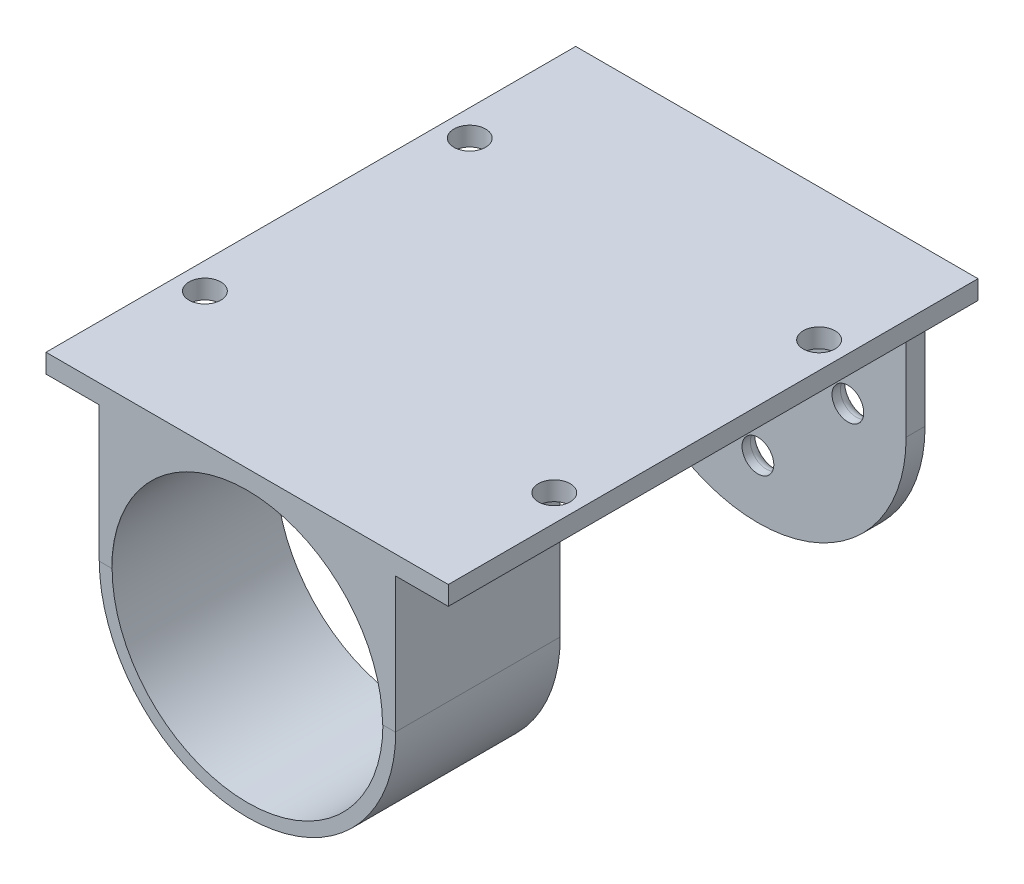
SolidWorks part; units mm, degrees
ref_plane "Front Plane" through (0, 0, 0) normal (0, 0, 1) x (1, 0, 0)
ref_plane "Top Plane" through (0, 0, 0) normal (0, 1, 0) x (1, 0, 0)
ref_plane "Right Plane" through (0, 0, 0) normal (1, 0, 0) x (0, 0, -1)
sketch "Sketch1" plane through (0, 0, 0) normal (0, 0, 1) x (1, 0, 0)
  circle A0 centre (0, 0) radius 14
  dimension "D1" = 28
extrude "Boss-Extrude1" add sketch "Sketch1" along normal blind 50
sketch "Sketch5" plane through (0, 0, 0) normal (0, 1, 0) x (1, 0, 0)
  line L0 (-14, 0) -> (14, 0)
  line L1 (-14, 0) -> (-14, -50.0349)
  line L2 (14, 0) -> (14, -50.0349)
  line L3 (-14, -50.0349) -> (14, -50.0349)
extrude "Boss-Extrude2" add sketch "Sketch5" along normal blind 21
sketch "Sketch2" plane through (0, 0, 50) normal (0, 0, 1) x (1, 0, 0)
  circle A0 centre (0, 0) radius 12.7918
  circle A1 centre (0, 0) radius 14 construction
  dimension "D1" = 1.2082
  dimension "D2" = 1.2082
extrude "Cut-Extrude1" cut sketch "Sketch2" against normal blind 48 contours A0
sketch "Sketch3" plane through (0, 0, 0) normal (0, 0, -1) x (-1, 0, 0)
  circle A0 centre (0, 0) radius 4
  dimension "D1" = 8
extrude "Cut-Extrude2" cut sketch "Sketch3" against normal blind 49
sketch "Sketch4" plane through (0, 0, 0) normal (0, 0, -1) x (-1, 0, 0)
  line L0 (-14, 0) -> (14, 0) construction
  line L1 (0, 14) -> (0, -14) construction
  line L2 (14, 0) -> (0, 14) construction
  line L3 (0, 14) -> (7, 7) construction
  line L4 (7, 7) -> (-9.8995, -9.8995) construction
  circle A0 centre (0, 0) radius 14 construction
  circle A1 centre (0, -8.5) radius 1.5
  circle A2 centre (0, 8.5) radius 1.5
  circle A3 centre (8.5, 0) radius 1.5
  circle A4 centre (-8.5, 0) radius 1.5
  dimension "D1" = 8.5
  dimension "D2" = 8.5
  dimension "D3" = 45
  dimension "D4" = 8.5
  dimension "D5" = 8.5
extrude "Cut-Extrude3" cut sketch "Sketch4" against normal blind 49
sketch "Sketch6" plane through (0, 0, 50.0349) normal (0, 0, 1) x (1, 0, 0)
  circle A1 centre (0, 0) radius 12.79
extrude "Cut-Extrude5" cut sketch "Sketch6" against normal blind 21
sketch "Sketch7" plane through (0, 0, 50.0349) normal (0, 0, 1) x (1, 0, 0)
  line L0 (-14, 21) -> (14, 21)
  line L1 (-14, 21) -> (-14, 16.3653)
  line L2 (14, 21) -> (14, 16.3653)
  line L3 (-14, 16.3653) -> (14, 16.3653)
extrude "Cut-Extrude6" cut sketch "Sketch7" against normal blind 53
sketch "Sketch8" plane through (14, 0, 0) normal (1, 0, 0) x (0, 0, -1)
  line L0 (-50.0349, 16.3653) -> (0, 16.3653)
  line L1 (-50.0349, 16.3653) -> (-50.0349, 12.7853)
  line L2 (0, 16.3653) -> (0, 12.7853)
  line L3 (-50.0349, 12.7853) -> (0, 12.7853)
  dimension "D1" = 3.58
extrude "Boss-Extrude3" add sketch "Sketch8" along normal blind 5
sketch "Sketch13" plane through (0, 12.7853, 0) normal (0, -1, 0) x (1, 0, 0)
  line L0 (16.5, 50.0349) -> (16.5, 0) construction
  line L1 (19, 50.0349) -> (14, 50.0349) construction
  line L2 (19, 0) -> (14, 0) construction
  line L3 (14, 25.0174) -> (19, 25.0174) construction
  line L4 (14, 50.0349) -> (14, 0) construction
  line L5 (19, 50.0349) -> (19, 0) construction
  line L6 (14, 25.0174) -> (19, 50.0349) construction
  line L7 (14, 25.0174) -> (19, 0) construction
  circle A0 centre (16.5, 37.5262) radius 1.5
  circle A1 centre (16.5, 12.5087) radius 1.5
  dimension "D1" = 5
extrude "Cut-Extrude7" cut sketch "Sketch13" against normal blind 5
sketch "Sketch14" plane through (-14, 0, 0) normal (-1, 0, 0) x (0, 0, 1)
  line L0 (0, 16.3653) -> (50.0349, 16.3653)
  line L1 (0, 16.3653) -> (0, 12.7853)
  line L2 (50.0349, 16.3653) -> (50.0349, 12.7853)
  line L3 (0, 12.7853) -> (50.0349, 12.7853)
  dimension "D1" = 3.58
extrude "Boss-Extrude4" add sketch "Sketch14" along normal blind 5
sketch "Sketch15" plane through (0, 12.7853, 0) normal (0, -1, 0) x (1, 0, 0)
  line L0 (-16.5, 0) -> (-16.5, 50.0349) construction
  line L1 (-19, 0) -> (-14, 0) construction
  line L2 (-19, 50.0349) -> (-14, 50.0349) construction
  line L3 (-19, 25.0174) -> (-14, 25.0174) construction
  line L4 (-19, 0) -> (-19, 50.0349) construction
  line L5 (-14, 0) -> (-14, 50.0349) construction
  line L6 (-14, 0) -> (-19, 25.0174) construction
  line L7 (-19, 25.0174) -> (-14, 50.0349) construction
  circle A0 centre (-16.5, 12.5087) radius 1.5
  circle A1 centre (-16.5, 37.5262) radius 1.5
extrude "Cut-Extrude8" cut sketch "Sketch15" against normal blind 5
fillet "Fillet1" radius 1 1 edges at (10, 0, 0)
fillet "Fillet2" radius 1 3 edges at (1.5, 8.5, 0) (-10, 0, 0) (-1.5, -8.5, 0)
sketch "Sketch16" plane through (0, 0, 0) normal (0, 0, -1) x (-1, 0, 0)
  line L0 (-19, 12.7853) -> (-19, 16.3653) construction
  line L1 (19, 16.3653) -> (-19, 16.3653)
  line L2 (19, 16.3653) -> (19, 14.5753)
  line L3 (19, 14.5753) -> (-19, 14.5753)
  line L4 (-19, 16.3653) -> (-19, 14.5753)
extrude "Cut-Extrude9" cut sketch "Sketch16" against normal through all both and the other way through all
sketch "Sketch19" plane through (14, 0, 0) normal (1, 0, 0) x (0, 0, -1)
  line L0 (0, 12.7853) -> (-1.79, 12.7853)
  line L1 (-50.0349, 12.7853) -> (0, 12.7853) construction
  line L2 (-50, -14) -> (0, -14) construction
  line L3 (-1.79, 12.7853) -> (-34.46, 12.7853)
  line L4 (-1.79, 12.7853) -> (-1.79, -14)
  line L5 (-1.79, -14) -> (-34.46, -14)
  line L6 (-34.46, 12.7853) -> (-34.46, -14)
  line M1 (0, 12.7853) -> (-50.0349, 12.7853)
  line M4 (-50, 0) -> (0, 0)
extrude "Cut-Extrude10" cut sketch "Sketch19" against normal through all both and the other way through all contours L6 L5 L4 M4 | L6 L4 M1 M4
